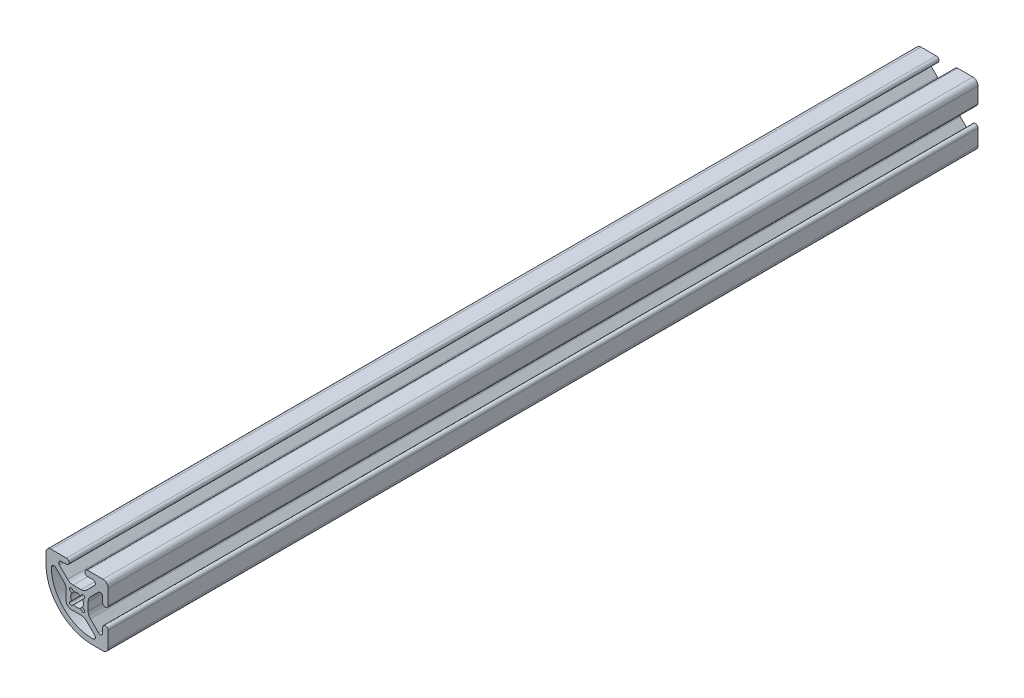
SolidWorks part; units mm, degrees
material "6105-T5 Aluminum"
ref_plane "Front Plane" through (0, 0, 0) normal (0, 0, 1) x (1, 0, 0)
ref_plane "Top Plane" through (0, 0, 0) normal (0, 1, 0) x (1, 0, 0)
ref_plane "Right Plane" through (0, 0, 0) normal (1, 0, 0) x (0, 0, -1)
sketch "Sketch2" plane through (0, 0, 0) normal (0, 0, 1) x (1, 0, 0)
  line L0 (-1.3405, -2.2319) -> (-1.9692, -2.8605)
  line L1 (-2.8605, -1.9692) -> (-2.2319, -1.3405)
  line L2 (-2.2319, 1.3405) -> (-2.8605, 1.9692)
  line L3 (-1.9692, 2.8605) -> (-1.3405, 2.2319)
  line L4 (1.3405, 2.2319) -> (1.9692, 2.8605)
  line L5 (2.8605, 1.9692) -> (2.2319, 1.3405)
  line L6 (2.2319, -1.3405) -> (2.8605, -1.9692)
  line L7 (1.9692, -2.8605) -> (1.3405, -2.2319)
  line L8 (3.8845, -5.4471) -> (7.1927, -8.7553)
  line L9 (-8.7553, 7.1927) -> (-5.4471, 3.8845)
  line L10 (-4.5172, 1.6395) -> (-4.5172, -2.3074)
  line L11 (-2.3074, -4.5172) -> (1.6395, -4.5172)
  line L12 (-4.3561, 12.7) -> (-10.5918, 12.7)
  line L13 (-12.7, 10.5918) -> (-12.7, 6.35)
  line L14 (6.35, -12.7) -> (10.5918, -12.7)
  line L15 (12.7, -10.5918) -> (12.7, -4.3561)
  line L16 (10.4902, -4.3561) -> (10.4902, -6.4749)
  line L17 (8.7558, -7.1933) -> (5.4471, -3.8846)
  line L18 (4.5172, -1.6396) -> (4.5172, 1.6396)
  line L19 (5.4471, 3.8846) -> (8.7558, 7.1933)
  line L20 (10.4902, 6.4749) -> (10.4902, 4.3561)
  line L21 (12.7, 4.3561) -> (12.7, 10.5918)
  line L22 (10.5918, 12.7) -> (4.3561, 12.7)
  line L23 (4.3561, 10.4902) -> (6.4749, 10.4902)
  line L24 (7.1933, 8.7558) -> (3.8846, 5.4471)
  line L25 (1.6396, 4.5172) -> (-1.6396, 4.5172)
  line L26 (-3.8846, 5.4471) -> (-7.1933, 8.7558)
  line L27 (-6.4749, 10.4902) -> (-4.3561, 10.4902)
  arc A0 (-2.8605, -1.9692) -> (-1.9692, -2.8605) centre (-2.4696, -2.4696) ccw
  arc A1 (-2.2319, 1.3405) -> (-2.2319, -1.3405) centre (0, 0) ccw
  arc A2 (-1.9692, 2.8605) -> (-2.8605, 1.9692) centre (-2.4696, 2.4696) ccw
  arc A3 (1.3405, 2.2319) -> (-1.3405, 2.2319) centre (0, 0) ccw
  arc A4 (2.8605, 1.9692) -> (1.9692, 2.8605) centre (2.4696, 2.4696) ccw
  arc A5 (2.2319, -1.3405) -> (2.2319, 1.3405) centre (0, 0) ccw
  arc A6 (1.9692, -2.8605) -> (2.8605, -1.9692) centre (2.4696, -2.4696) ccw
  arc A7 (-1.3405, -2.2319) -> (1.3405, -2.2319) centre (0, 0) ccw
  arc A8 (6.4823, -10.4897) -> (7.1927, -8.7553) centre (6.4743, -9.4737) ccw
  arc A9 (-10.4897, 6.4823) -> (6.4823, -10.4897) centre (6.35, 6.35) ccw
  arc A10 (-8.7553, 7.1927) -> (-10.4897, 6.4823) centre (-9.4737, 6.4743) ccw
  arc A11 (-4.5172, 1.6395) -> (-5.4471, 3.8845) centre (-7.6922, 1.6395) ccw
  arc A12 (-4.5172, -2.3074) -> (-2.3074, -4.5172) centre (-2.3074, -2.3074) ccw
  arc A13 (3.8845, -5.4471) -> (1.6395, -4.5172) centre (1.6395, -7.6922) ccw
  arc A14 (-4.3561, 10.4902) -> (-4.3561, 12.7) centre (-4.3561, 11.5951) ccw
  arc A15 (-10.5918, 12.7) -> (-12.7, 10.5918) centre (-10.5918, 10.5918) ccw
  arc A16 (-12.7, 6.35) -> (6.35, -12.7) centre (6.35, 6.35) ccw
  arc A17 (10.5918, -12.7) -> (12.7, -10.5918) centre (10.5918, -10.5918) ccw
  arc A18 (12.7, -4.3561) -> (10.4902, -4.3561) centre (11.5951, -4.3561) ccw
  arc A19 (8.7558, -7.1933) -> (10.4902, -6.4749) centre (9.4742, -6.4749) ccw
  arc A20 (4.5172, -1.6396) -> (5.4471, -3.8846) centre (7.6922, -1.6396) ccw
  arc A21 (5.4471, 3.8846) -> (4.5172, 1.6396) centre (7.6922, 1.6396) ccw
  arc A22 (10.4902, 6.4749) -> (8.7558, 7.1933) centre (9.4742, 6.4749) ccw
  arc A23 (10.4902, 4.3561) -> (12.7, 4.3561) centre (11.5951, 4.3561) ccw
  arc A24 (12.7, 10.5918) -> (10.5918, 12.7) centre (10.5918, 10.5918) ccw
  arc A25 (4.3561, 12.7) -> (4.3561, 10.4902) centre (4.3561, 11.5951) ccw
  arc A26 (7.1933, 8.7558) -> (6.4749, 10.4902) centre (6.4749, 9.4742) ccw
  arc A27 (1.6396, 4.5172) -> (3.8846, 5.4471) centre (1.6396, 7.6922) ccw
  arc A28 (-3.8846, 5.4471) -> (-1.6396, 4.5172) centre (-1.6396, 7.6922) ccw
  arc A29 (-6.4749, 10.4902) -> (-7.1933, 8.7558) centre (-6.4749, 9.4742) ccw
  dimension "D1" = 0.635
  dimension "D2" = 2.6035
  dimension "D3" = 1.016
  dimension "D4" = 16.8402
  dimension "D5" = 3.175
  dimension "D6" = 2.2098
  dimension "D7" = 1.1049
  dimension "D8" = 2.1082
  dimension "D9" = 19.05
  dimension "D10" = 1.3405
  dimension "D11" = 1.6395
  dimension "D12" = 1.6396
  dimension "D13" = 1.9692
  dimension "D14" = 4.3561
  dimension "D15" = 4.5172
  dimension "D16" = 1.6395
  dimension "D17" = 11.5951
extrude "Extrude1" add sketch "Sketch2" against normal blind 355.6
